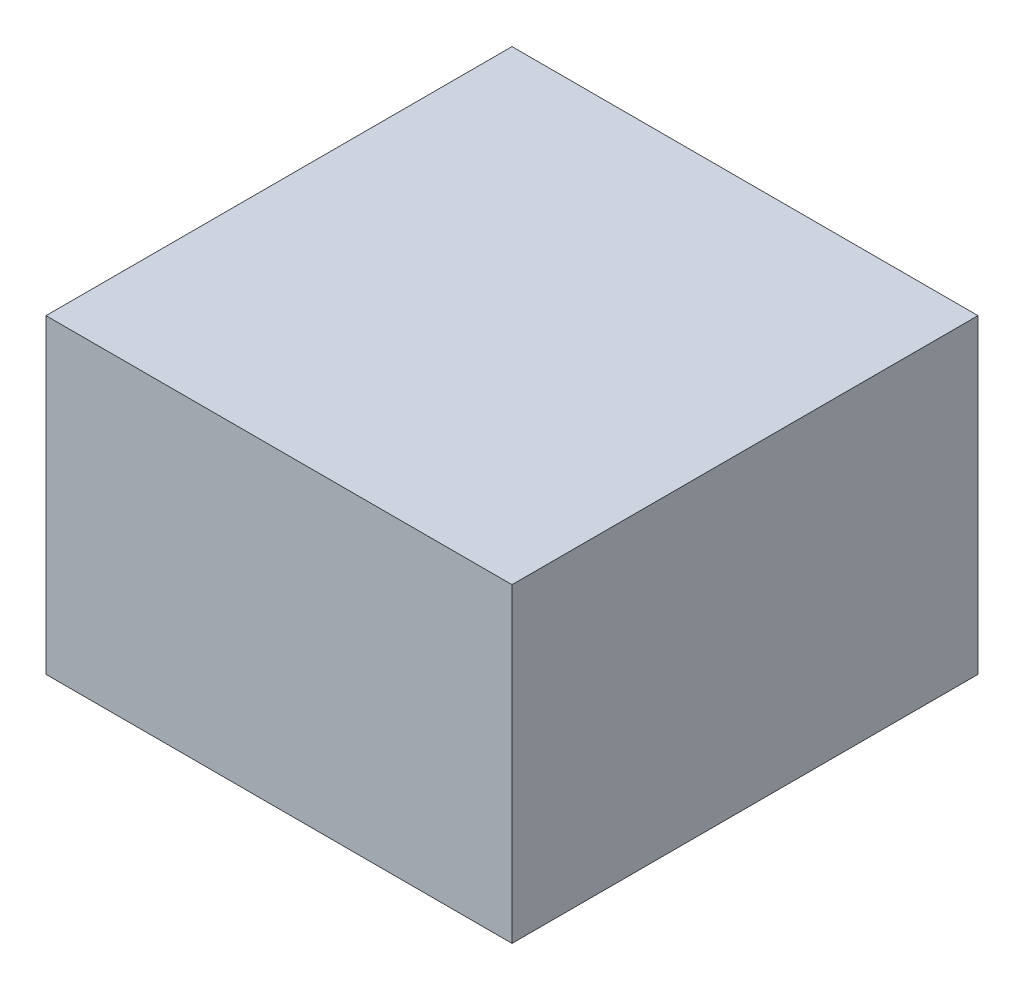
SolidWorks part; units mm, degrees
ref_plane "Plan de face" through (0, 0, 0) normal (0, 0, 1) x (1, 0, 0)
ref_plane "Plan de dessus" through (0, 0, 0) normal (0, 1, 0) x (1, 0, 0)
ref_plane "Plan de droite" through (0, 0, 0) normal (1, 0, 0) x (0, 0, -1)
sketch "Esquisse1" plane through (0, 0, 0) normal (0, 0, 1) x (1, 0, 0)
  line L1 (0, 0) -> (-30, 0)
  line L2 (0, 0) -> (0, 20)
  line L3 (0, 20) -> (-30, 20)
  line L4 (-30, 0) -> (-30, 20)
  dimension "D1" = 30
  dimension "D2" = 20
extrude "Boss.-Extru.1" add sketch "Esquisse1" along normal blind 30
sketch "Sketch1" plane through (0, 0, 0) normal (0, 1, 0) x (1, 0, 0)
  line L0 (-30, -30) -> (-30, 0) construction
  circle A0 centre (-20, -10) radius 5
  dimension "D1" = 10
  dimension "D2" = 10
  dimension "D3" = 10
extrude "Boss-Extrude1" add sketch "Sketch1" against normal blind 10
